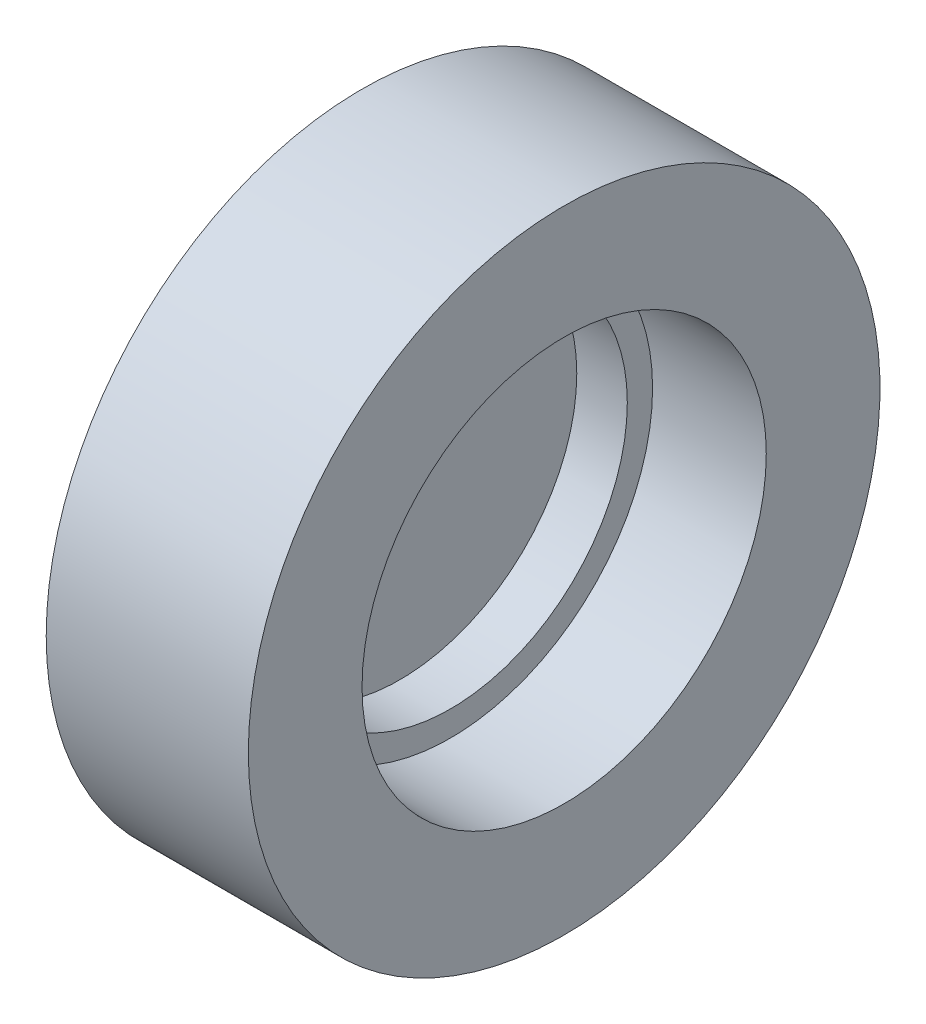
SolidWorks part; units mm, degrees
material "AISI 1020"
ref_plane "Plano frontal" through (0, 0, 0) normal (0, 0, 1) x (1, 0, 0)
ref_plane "Plano superior" through (0, 0, 0) normal (0, 1, 0) x (1, 0, 0)
ref_plane "Plano direito" through (0, 0, 0) normal (1, 0, 0) x (0, 0, -1)
sketch "Esboço1" plane through (0, 0, 0) normal (0, 0, 1) x (1, 0, 0)
  line L0 (0, 0) -> (0, 25)
  line L1 (0, 25) -> (16, 25)
  line L2 (16, 25) -> (16, 16)
  line L3 (16, 16) -> (7, 16)
  line L4 (7, 16) -> (7, 14)
  line L5 (7, 14) -> (3, 14)
  line L6 (3, 14) -> (3, 0)
  line L7 (0, 0) -> (30.8752, 0) construction
  line L8 (0, 0) -> (3, 0)
  dimension "D1" = 9
  dimension "D2" = 4
  dimension "D3" = 32
  dimension "D4" = 28
  dimension "D5" = 16
  dimension "D6" = 50
revolve "Revolução1" add sketch "Esboço1" angle 360 about L7
